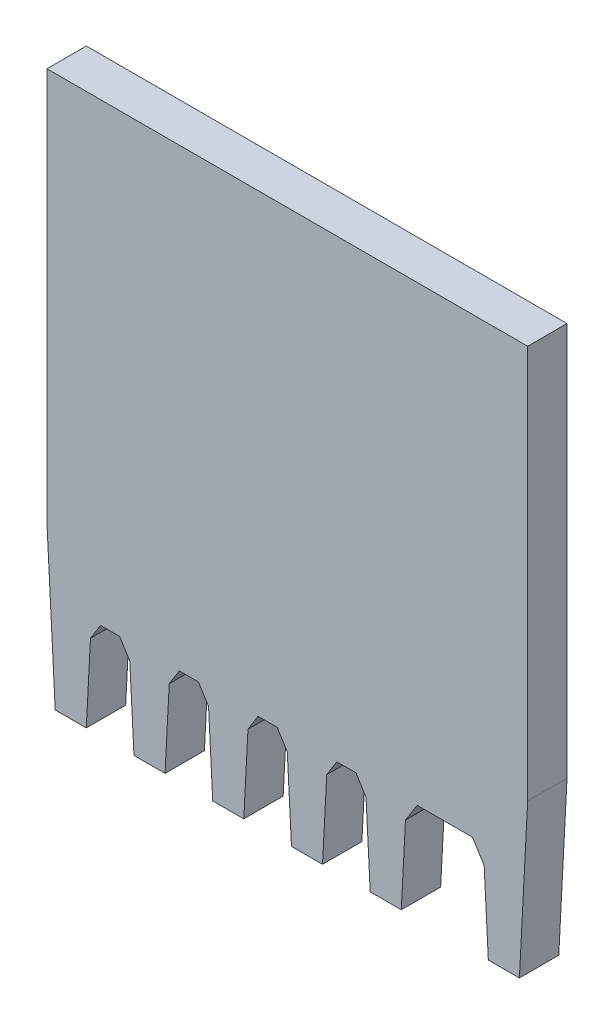
SolidWorks part; units mm, degrees
ref_plane "Front Plane" through (0, 0, 0) normal (0, 0, 1) x (1, 0, 0)
ref_plane "Top Plane" through (0, 0, 0) normal (0, 1, 0) x (1, 0, 0)
ref_plane "Right Plane" through (0, 0, 0) normal (1, 0, 0) x (0, 0, -1)
sketch "Sketch1" plane through (0, 0, 0) normal (0, 0, 1) x (1, 0, 0)
  line L0 (0, 0) -> (0, 21) construction
  line L1 (0, 21) -> (18.3124, 21) construction
  line L2 (18.3124, 21) -> (18.3124, 0) construction
  line L3 (18.3124, 0) -> (0, 0) construction
  line L4 (0, 3) -> (18.3124, 3) construction
  line L5 (0, 6) -> (18.3124, 6) construction
  line L6 (0.9062, 6) -> (0.9062, 0) construction
  line L7 (3.9062, 6) -> (3.9062, 0) construction
  line L8 (6.9062, 6) -> (6.9062, 0) construction
  line L9 (9.9062, 6) -> (9.9062, 0) construction
  line L10 (12.9062, 6) -> (12.9062, 0) construction
  line L11 (17.4062, 6) -> (17.4062, 0) construction
  line L12 (0.9062, 3) -> (3.9062, 3) construction
  line L13 (3.9062, 3) -> (6.9062, 3) construction
  line L14 (6.9062, 3) -> (9.9062, 3) construction
  line L15 (9.9062, 3) -> (12.9062, 3) construction
  line L16 (12.9062, 3) -> (17.4062, 3) construction
  line L17 (0.9062, 3) -> (0, 3) construction
  line L18 (17.4062, 3) -> (18.3124, 3) construction
  line L19 (2.4062, 3) -> (2.4062, 0) construction
  line L20 (5.4062, 3) -> (5.4062, 0) construction
  line L21 (8.4062, 3) -> (8.4062, 0) construction
  line L22 (11.4062, 3) -> (11.4062, 0) construction
  line L23 (15.1562, 3) -> (15.1562, 0) construction
  line L24 (14.4062, 3.75) -> (15.9062, 3.75) construction
  line L25 (0, 6) -> (0.3144, 0)
  line L26 (0.3144, 0) -> (1.4979, 0)
  line L27 (1.4979, 0) -> (1.6572, 3.0393)
  line L28 (3.1552, 3.0393) -> (3.3144, 0)
  line L29 (3.3144, 0) -> (4.4979, 0)
  line L30 (4.4979, 0) -> (4.6572, 3.0393)
  line L31 (6.1552, 3.0393) -> (6.3144, 0)
  line L32 (6.3144, 0) -> (7.4979, 0)
  line L33 (7.4979, 0) -> (7.6572, 3.0393)
  line L34 (9.1552, 3.0393) -> (9.3144, 0)
  line L35 (9.3144, 0) -> (10.4979, 0)
  line L36 (10.4979, 0) -> (10.6572, 3.0393)
  line L37 (12.1552, 3.0393) -> (12.3144, 0)
  line L38 (12.3144, 0) -> (13.4979, 0)
  line L39 (13.4979, 0) -> (13.6572, 3.0393)
  line L40 (16.6552, 3.0393) -> (16.8144, 0)
  line L41 (16.8144, 0) -> (17.9979, 0)
  line L42 (17.9979, 0) -> (18.3124, 6)
  line L44 (1.6572, 3.0393) -> (2.0426, 3.656)
  line L45 (0, 6) -> (0, 21)
  line L46 (0, 21) -> (18.3124, 21)
  line L47 (18.3124, 21) -> (18.3124, 6)
  line L48 (9.1562, 21) -> (9.1562, 6) construction
  line L49 (2.0426, 3.656) -> (2.7698, 3.656)
  line L50 (2.7698, 3.656) -> (3.1552, 3.0393)
  line L51 (4.6572, 3.0393) -> (5.0426, 3.656)
  line L52 (5.0426, 3.656) -> (5.7698, 3.656)
  line L53 (5.7698, 3.656) -> (6.1552, 3.0393)
  line L54 (7.6572, 3.0393) -> (8.0426, 3.656)
  line L55 (8.0426, 3.656) -> (8.7698, 3.656)
  line L56 (8.7698, 3.656) -> (9.1552, 3.0393)
  line L57 (10.6572, 3.0393) -> (11.0426, 3.656)
  line L58 (11.0426, 3.656) -> (11.7698, 3.656)
  line L59 (11.7698, 3.656) -> (12.1552, 3.0393)
  line L60 (13.6572, 3.0393) -> (14.1013, 3.75)
  line L61 (14.1013, 3.75) -> (16.211, 3.75)
  line L62 (16.211, 3.75) -> (16.6552, 3.0393)
  arc A0 (3.1552, 3.0393) -> (1.6572, 3.0393) centre (2.4062, 3) ccw construction
  arc A1 (6.1552, 3.0393) -> (4.6572, 3.0393) centre (5.4062, 3) ccw construction
  arc A2 (9.1552, 3.0393) -> (7.6572, 3.0393) centre (8.4062, 3) ccw construction
  arc A3 (12.1552, 3.0393) -> (10.6572, 3.0393) centre (11.4062, 3) ccw construction
  arc A4 (13.6572, 3.0393) -> (14.4062, 3.75) centre (14.4062, 3) cw construction
  arc A5 (16.6552, 3.0393) -> (15.9062, 3.75) centre (15.9062, 3) ccw construction
  dimension "D7" = 0.75
  dimension "D1" = 3
  dimension "D2" = 6
  dimension "D3" = 15
  dimension "D4" = 3
  dimension "D6" = 4.5
  dimension "D8" = 3
  dimension "D9" = 18.3124
  dimension "D10" = 21
extrude "Boss-Extrude1" add sketch "Sketch1" along normal blind 1.5
